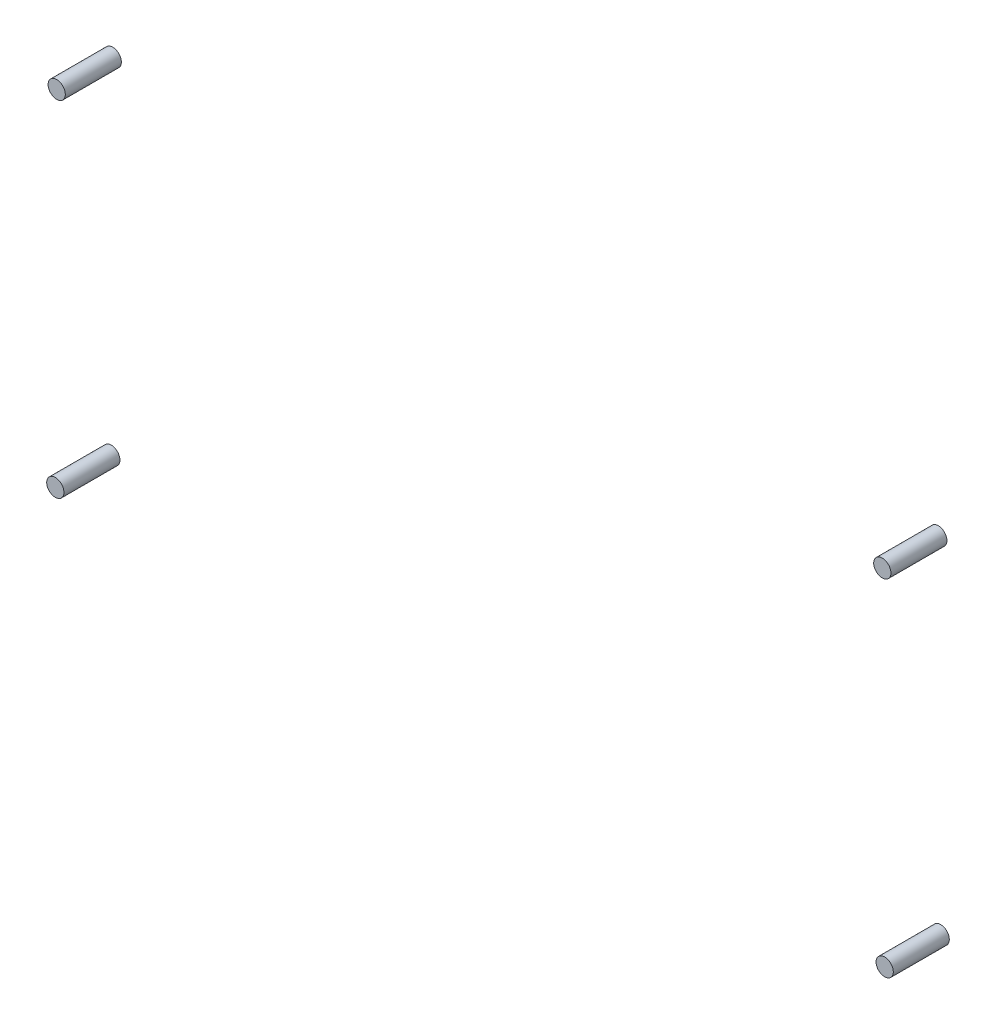
SolidWorks part; units mm, degrees
ref_plane "前视基准面" through (0, 0, 0) normal (0, 0, 1) x (1, 0, 0)
ref_plane "上视基准面" through (0, 0, 0) normal (0, 1, 0) x (1, 0, 0)
ref_plane "右视基准面" through (0, 0, 0) normal (1, 0, 0) x (0, 0, -1)
sketch "草图2" plane through (0, 0, 1.6001) normal (0, 0, 1) x (1, 0, 0)
  circle A0 centre (47.0174, -148.7966) radius 2
  dimension "D1" = 4
extrude "凸台-拉伸1" add sketch "草图2" along normal blind 13
sketch "草图4" plane through (0, 0, 1.6001) normal (0, 0, 1) x (1, 0, 0)
  circle A0 centre (238.6035, -149.1776) radius 2
  dimension "D1" = 4
extrude "凸台-拉伸2" add sketch "草图4" along normal blind 13 separate body
sketch "草图5" plane through (0, 0, 1.6001) normal (0, 0, 1) x (1, 0, 0)
  circle A0 centre (239.1565, -229.0607) radius 2
  circle A1 centre (46.6938, -228.9337) radius 2
  dimension "D1" = 4
  dimension "D2" = 4
extrude "凸台-拉伸3" add sketch "草图5" along normal blind 13 separate body
